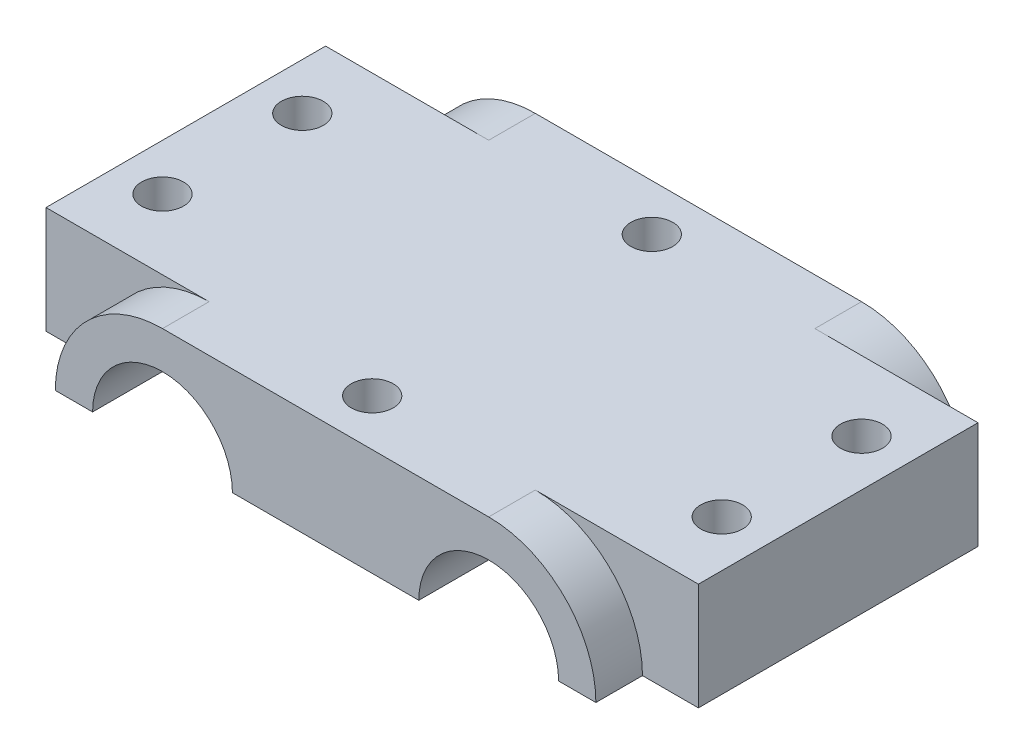
SolidWorks part; units mm, degrees
ref_plane "Front Plane" through (0, 0, 0) normal (0, 0, 1) x (1, 0, 0)
ref_plane "Top Plane" through (0, 0, 0) normal (0, 1, 0) x (1, 0, 0)
ref_plane "Right Plane" through (0, 0, 0) normal (1, 0, 0) x (0, 0, -1)
sketch "Sketch1" plane through (0, 0, 0) normal (0, 0, 1) x (1, 0, 0)
  line L1 (35, 5.75) -> (-35, 5.75)
  line L2 (35, 5.75) -> (35, -5.75)
  line L3 (35, -5.75) -> (-35, -5.75)
  line L4 (-35, 5.75) -> (-35, -5.75)
  line L5 (35, 5.75) -> (-35, -5.75) construction
  line L6 (35, -5.75) -> (-35, 5.75) construction
  point P0 (0, 0)
  dimension "D1" = 70
  dimension "D2" = 11.5
extrude "Boss-Extrude1" add sketch "Sketch1" along normal mid plane 40
sketch "Sketch2" plane through (0, 0, 20) normal (0, 0, 1) x (1, 0, 0)
  line L0 (-35, -5.75) -> (35, -5.75) construction
  line L1 (-25, -5.75) -> (-10, -5.75)
  line L2 (10, -5.75) -> (25, -5.75)
  line L3 (0, 0) -> (0, 13.3479) construction
  arc A0 (10, -5.75) -> (25, -5.75) centre (17.5, -5.75) cw
  arc A1 (-10, -5.75) -> (-25, -5.75) centre (-17.5, -5.75) ccw
  dimension "D1" = 7.5
  dimension "D2" = 35
extrude "Cut-Extrude1" cut sketch "Sketch2" against normal up to next
sketch "Sketch3" plane through (0, 0, 20) normal (0, 0, 1) x (1, 0, 0)
  line L0 (25, -5.75) -> (35, -5.75) construction
  line L1 (35, 5.75) -> (-35, 5.75) construction
  line L2 (-35, 5.75) -> (-35, -5.75) construction
  line L3 (-35, -5.75) -> (-25, -5.75) construction
  line L4 (35, -5.75) -> (35, 5.75) construction
  line L5 (-35, 5.75) -> (-35, -5.75)
  line L6 (-35, -5.75) -> (-29, -5.75)
  line L7 (29, -5.75) -> (35, -5.75)
  line L8 (35, -5.75) -> (35, 5.75)
  line L9 (35, 5.75) -> (17.5, 5.75)
  line L10 (0, 0) -> (0, -17.2315) construction
  line L11 (-17.5, 5.75) -> (-35, 5.75)
  arc A0 (29, -5.75) -> (17.5, 5.75) centre (17.5, -5.75) ccw
  arc A1 (-29, -5.75) -> (-17.5, 5.75) centre (-17.5, -5.75) cw
extrude "Cut-Extrude2" cut sketch "Sketch3" against normal blind 5
mirror "Mirror1" about plane through (0, 0, 0) normal (0, 0, 1) of "Cut-Extrude2"
hole_wizard "Hole1" positions "Sketch6" profile "Sketch5" legacy end condition through all
sketch "Sketch6" plane through (0, 5.75, 0) normal (0, 1, 0) x (1, 0, 0)
  point P0 (30, -7.5)
  dimension "D1" = 30
  dimension "D2" = 7.5
sketch "Sketch5" plane through (30, 5.75, 7.5) normal (1, 0, 0) x (0, 0, 1)
  line L0 (0, 0) -> (0, 11.5)
  line L1 (0, 11.5) -> (2.25, 11.5)
  line L2 (2.25, 11.5) -> (2.25, 0)
  line L3 (2.25, 0) -> (0, 0)
  line L4 (0, 110) -> (0, -10) construction
  dimension "Diameter" = 4.5
  dimension "Depth" = 11.5
pattern_linear "LPattern1" count 2 spacing 60 along (-1, 0, 0) count 2 spacing 15 along (0, 0, -1) of "Hole1"
hole_wizard "Hole2" positions "Sketch7" profile "Sketch8" legacy end condition through all
sketch "Sketch7" plane through (0, 5.75, 0) normal (0, 1, 0) x (1, 0, 0)
  point P0 (0, -15)
  dimension "D1" = 15
sketch "Sketch8" plane through (0, 5.75, 15) normal (1, 0, 0) x (0, 0, 1)
  line L0 (0, 0) -> (0, 11.5)
  line L1 (0, 11.5) -> (2.25, 11.5)
  line L2 (2.25, 11.5) -> (2.25, 0)
  line L3 (2.25, 0) -> (0, 0)
  line L4 (0, 110) -> (0, -10) construction
  dimension "Diameter" = 4.5
  dimension "Depth" = 11.5
mirror "Mirror2" about plane through (0, 0, 0) normal (0, 0, 1) of "Hole2"
